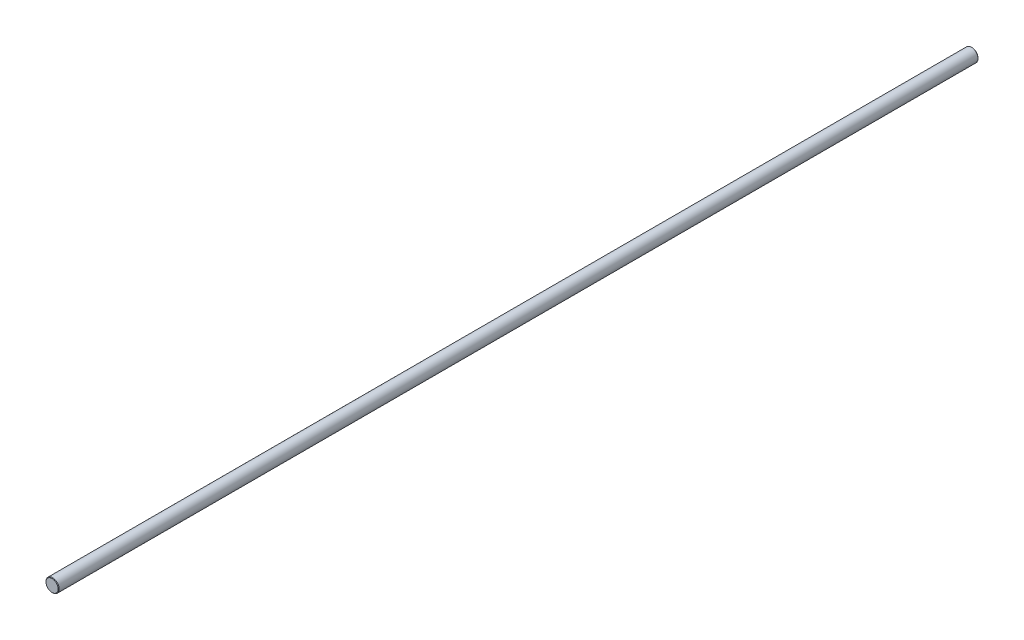
SolidWorks part; units mm, degrees
ref_plane "Front Plane" through (0, 0, 0) normal (0, 0, 1) x (1, 0, 0)
ref_plane "Top Plane" through (0, 0, 0) normal (0, 1, 0) x (1, 0, 0)
ref_plane "Right Plane" through (0, 0, 0) normal (1, 0, 0) x (0, 0, -1)
sketch "Sketch1" plane through (0, 0, 0) normal (0, 0, 1) x (1, 0, 0)
  circle A0 centre (0, 0) radius 10
  dimension "D1" = 20
extrude "Boss-Extrude1" add sketch "Sketch1" along normal mid plane 1397
chamfer "Chamfer1" distance 0.762 angle 45 2 edges at (10, 0, -698.5) (10, 0, 698.5)
